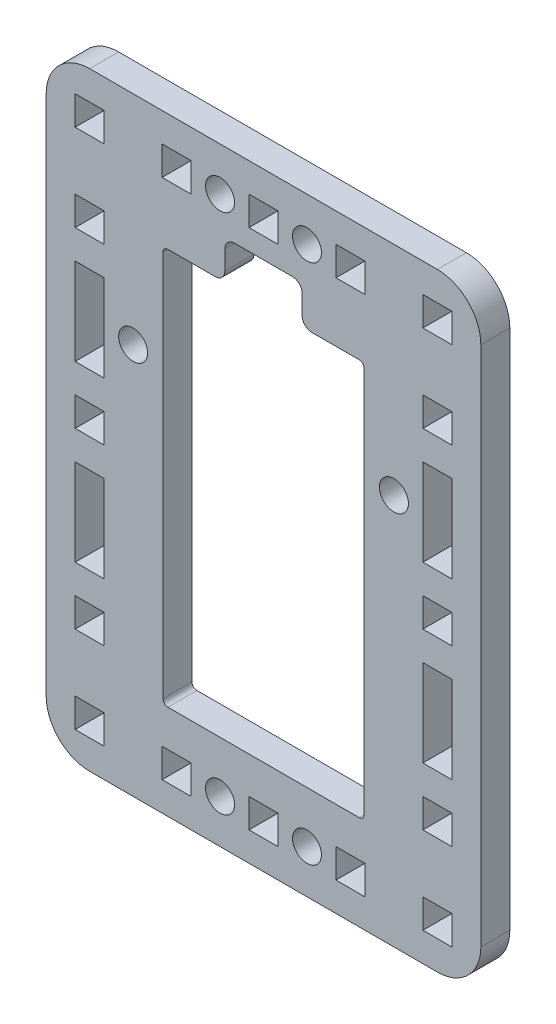
SolidWorks part; units mm, degrees
ref_plane "Alzado" through (0, 0, 0) normal (0, 0, 1) x (1, 0, 0)
ref_plane "Planta" through (0, 0, 0) normal (0, 1, 0) x (1, 0, 0)
ref_plane "Vista lateral" through (0, 0, 0) normal (1, 0, 0) x (0, 0, -1)
sketch "Model" plane through (0, 0, 0) normal (0, 0, 1) x (1, 0, 0)
  line L0 (17.1918, 237.5317) -> (20.1918, 237.5317)
  line L1 (17.1918, 240.5317) -> (17.1918, 237.5317)
  line L2 (20.1918, 240.5317) -> (17.1918, 240.5317)
  line L3 (20.1918, 237.5317) -> (20.1918, 240.5317)
  line L4 (17.1918, 246.5317) -> (20.1918, 246.5317)
  line L5 (17.1918, 249.5317) -> (17.1918, 246.5317)
  line L6 (20.1918, 249.5317) -> (17.1918, 249.5317)
  line L7 (20.1918, 246.5317) -> (20.1918, 249.5317)
  line L8 (17.1918, 291.5317) -> (20.1918, 291.5317)
  line L9 (17.1918, 294.5317) -> (17.1918, 291.5317)
  line L10 (20.1918, 294.5317) -> (17.1918, 294.5317)
  line L11 (20.1918, 291.5317) -> (20.1918, 294.5317)
  line L12 (53.1918, 237.5317) -> (56.1918, 237.5317)
  line L13 (53.1918, 240.5317) -> (53.1918, 237.5317)
  line L14 (56.1918, 240.5317) -> (53.1918, 240.5317)
  line L15 (56.1918, 237.5317) -> (56.1918, 240.5317)
  line L16 (53.1918, 246.5317) -> (56.1918, 246.5317)
  line L17 (53.1918, 249.5317) -> (53.1918, 246.5317)
  line L18 (56.1918, 249.5317) -> (53.1918, 249.5317)
  line L19 (56.1918, 246.5317) -> (56.1918, 249.5317)
  line L20 (53.1918, 291.5317) -> (56.1918, 291.5317)
  line L21 (53.1918, 294.5317) -> (53.1918, 291.5317)
  line L22 (56.1918, 294.5317) -> (53.1918, 294.5317)
  line L23 (56.1918, 291.5317) -> (56.1918, 294.5317)
  line L24 (44.1918, 237.5317) -> (47.1918, 237.5317)
  line L25 (44.1918, 240.5317) -> (44.1918, 237.5317)
  line L26 (47.1918, 240.5317) -> (44.1918, 240.5317)
  line L27 (47.1918, 237.5317) -> (47.1918, 240.5317)
  line L28 (44.1918, 291.5317) -> (47.1918, 291.5317)
  line L29 (44.1918, 294.5317) -> (44.1918, 291.5317)
  line L30 (47.1918, 294.5317) -> (44.1918, 294.5317)
  line L31 (47.1918, 291.5317) -> (47.1918, 294.5317)
  line L32 (17.1918, 264.5317) -> (20.1918, 264.5317)
  line L33 (17.1918, 267.5317) -> (17.1918, 264.5317)
  line L34 (20.1918, 267.5317) -> (17.1918, 267.5317)
  line L35 (20.1918, 264.5317) -> (20.1918, 267.5317)
  line L36 (17.1918, 282.5317) -> (20.1918, 282.5317)
  line L37 (17.1918, 285.5317) -> (17.1918, 282.5317)
  line L38 (20.1918, 285.5317) -> (17.1918, 285.5317)
  line L39 (20.1918, 282.5317) -> (20.1918, 285.5317)
  line L40 (53.1918, 264.5317) -> (56.1918, 264.5317)
  line L41 (53.1918, 267.5317) -> (53.1918, 264.5317)
  line L42 (56.1918, 267.5317) -> (53.1918, 267.5317)
  line L43 (56.1918, 264.5317) -> (56.1918, 267.5317)
  line L44 (53.1918, 282.5317) -> (56.1918, 282.5317)
  line L45 (53.1918, 285.5317) -> (53.1918, 282.5317)
  line L46 (56.1918, 285.5317) -> (53.1918, 285.5317)
  line L47 (56.1918, 282.5317) -> (56.1918, 285.5317)
  line L48 (35.1918, 237.5317) -> (38.1918, 237.5317)
  line L49 (35.1918, 240.5317) -> (35.1918, 237.5317)
  line L50 (38.1918, 240.5317) -> (35.1918, 240.5317)
  line L51 (38.1918, 237.5317) -> (38.1918, 240.5317)
  line L52 (35.1918, 291.5317) -> (38.1918, 291.5317)
  line L53 (35.1918, 294.5317) -> (35.1918, 291.5317)
  line L54 (38.1918, 294.5317) -> (35.1918, 294.5317)
  line L55 (38.1918, 291.5317) -> (38.1918, 294.5317)
  line L56 (26.1918, 237.5317) -> (29.1918, 237.5317)
  line L57 (26.1918, 240.5317) -> (26.1918, 237.5317)
  line L58 (29.1918, 240.5317) -> (26.1918, 240.5317)
  line L59 (29.1918, 237.5317) -> (29.1918, 240.5317)
  line L60 (26.1918, 291.5317) -> (29.1918, 291.5317)
  line L61 (26.1918, 294.5317) -> (26.1918, 291.5317)
  line L62 (29.1918, 294.5317) -> (26.1918, 294.5317)
  line L63 (29.1918, 291.5317) -> (29.1918, 294.5317)
  line L64 (20.1918, 261.5317) -> (17.1918, 261.5317)
  line L65 (53.1918, 252.5317) -> (56.1918, 252.5317)
  line L66 (53.1918, 261.5317) -> (53.1918, 252.5317)
  line L67 (56.1918, 252.5317) -> (56.1918, 261.5317)
  line L68 (56.1918, 261.5317) -> (53.1918, 261.5317)
  line L69 (20.1918, 279.5317) -> (17.1918, 279.5317)
  line L70 (56.1918, 279.5317) -> (53.1918, 279.5317)
  line L71 (14.1918, 239.0317) -> (14.1918, 293.0317)
  line L72 (59.1918, 239.0317) -> (59.1918, 293.0317)
  line L73 (18.6918, 234.5317) -> (54.6918, 234.5317)
  line L74 (18.6918, 297.5317) -> (54.6918, 297.5317)
  line L75 (26.2918, 284.8817) -> (26.2918, 244.8317)
  line L76 (31.6918, 285.3817) -> (26.7918, 285.3817)
  line L77 (47.0918, 244.8317) -> (47.0918, 284.8817)
  line L78 (26.7918, 244.3317) -> (46.5918, 244.3317)
  line L79 (46.5918, 285.3817) -> (41.6918, 285.3817)
  line L80 (32.6918, 286.3817) -> (32.6918, 288.3817)
  line L81 (40.6918, 286.3817) -> (40.6918, 288.3817)
  line L82 (33.6918, 289.3817) -> (39.6918, 289.3817)
  line L83 (17.1918, 270.5317) -> (20.1918, 270.5317)
  line L84 (17.1918, 279.5317) -> (17.1918, 270.5317)
  line L85 (20.1918, 270.5317) -> (20.1918, 279.5317)
  line L86 (53.1918, 270.5317) -> (56.1918, 270.5317)
  line L87 (53.1918, 279.5317) -> (53.1918, 270.5317)
  line L88 (56.1918, 270.5317) -> (56.1918, 279.5317)
  line L89 (17.1918, 252.5317) -> (20.1918, 252.5317)
  line L90 (17.1918, 261.5317) -> (17.1918, 252.5317)
  line L91 (20.1918, 252.5317) -> (20.1918, 261.5317)
  arc A0 (18.6918, 297.5317) -> (14.1918, 293.0317) centre (18.6918, 293.0317) ccw
  arc A1 (59.1918, 293.0317) -> (54.6918, 297.5317) centre (54.6918, 293.0317) ccw
  arc A2 (14.1918, 239.0317) -> (18.6918, 234.5317) centre (18.6918, 239.0317) ccw
  arc A3 (54.6918, 234.5317) -> (59.1918, 239.0317) centre (54.6918, 239.0317) ccw
  arc A4 (26.2918, 244.8317) -> (26.7918, 244.3317) centre (26.7918, 244.8317) ccw
  arc A5 (26.7918, 285.3817) -> (26.2918, 284.8817) centre (26.7918, 284.8817) ccw
  arc A6 (46.5918, 244.3317) -> (47.0918, 244.8317) centre (46.5918, 244.8317) ccw
  arc A7 (47.0918, 284.8817) -> (46.5918, 285.3817) centre (46.5918, 284.8817) ccw
  circle A8 centre (32.1918, 239.0317) radius 1.5
  circle A9 centre (41.1918, 239.0317) radius 1.5
  circle A10 centre (32.1918, 293.0317) radius 1.5
  circle A11 centre (41.1918, 293.0317) radius 1.5
  arc A12 (31.6918, 285.3817) -> (32.6918, 286.3817) centre (31.6918, 286.3817) ccw
  arc A13 (40.6918, 286.3817) -> (41.6918, 285.3817) centre (41.6918, 286.3817) ccw
  arc A14 (40.6918, 288.3817) -> (39.6918, 289.3817) centre (39.6918, 288.3817) ccw
  arc A15 (33.6918, 289.3817) -> (32.6918, 288.3817) centre (33.6918, 288.3817) ccw
  circle A16 centre (50.1918, 275.0317) radius 1.5
  circle A17 centre (23.1918, 275.0317) radius 1.5
extrude "Saliente-Extruir1" add sketch "Model" along normal blind 3
